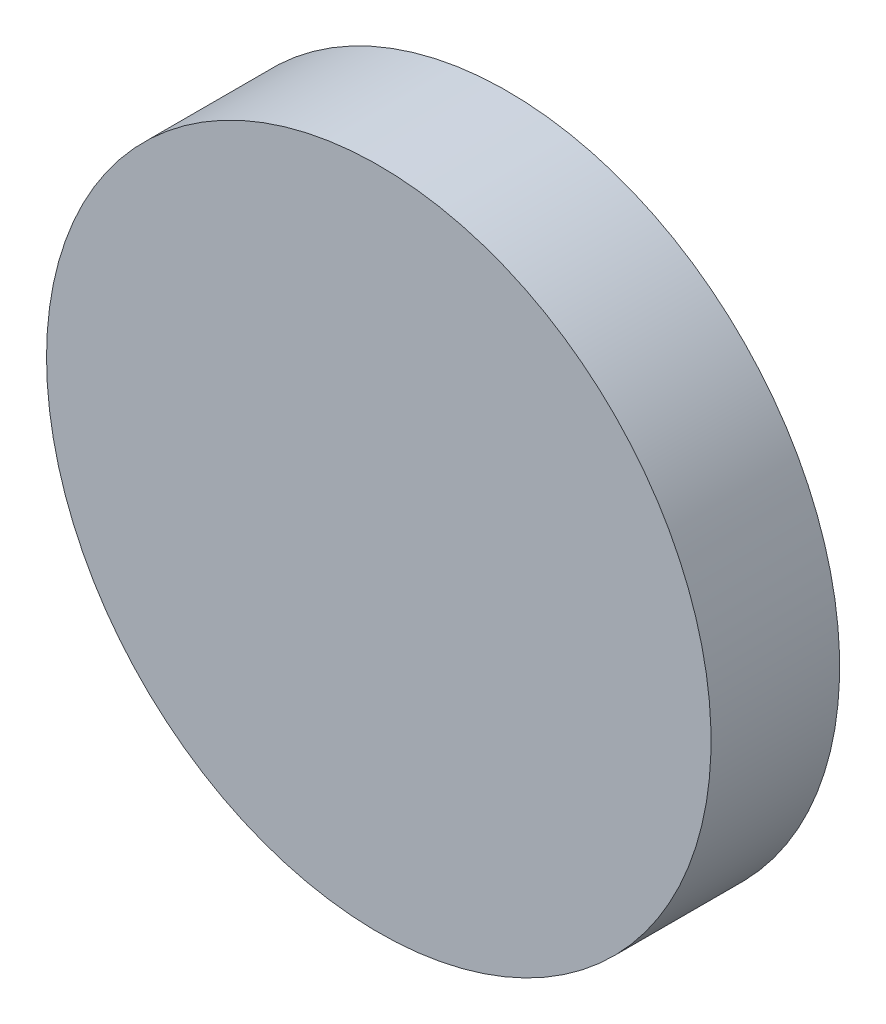
SolidWorks part; units mm, degrees
material "Polyurethane Foam Flexible"
ref_plane "Front Plane" through (0, 0, 0) normal (0, 0, 1) x (1, 0, 0)
ref_plane "Top Plane" through (0, 0, 0) normal (0, 1, 0) x (1, 0, 0)
ref_plane "Right Plane" through (0, 0, 0) normal (1, 0, 0) x (0, 0, -1)
sketch "Sketch1" plane through (0, 0, 0) normal (0, 0, 1) x (1, 0, 0)
  circle A0 centre (0, 0) radius 78.74
  dimension "D1" = 157.48
extrude "Boss-Extrude1" add sketch "Sketch1" along normal blind 30.48
